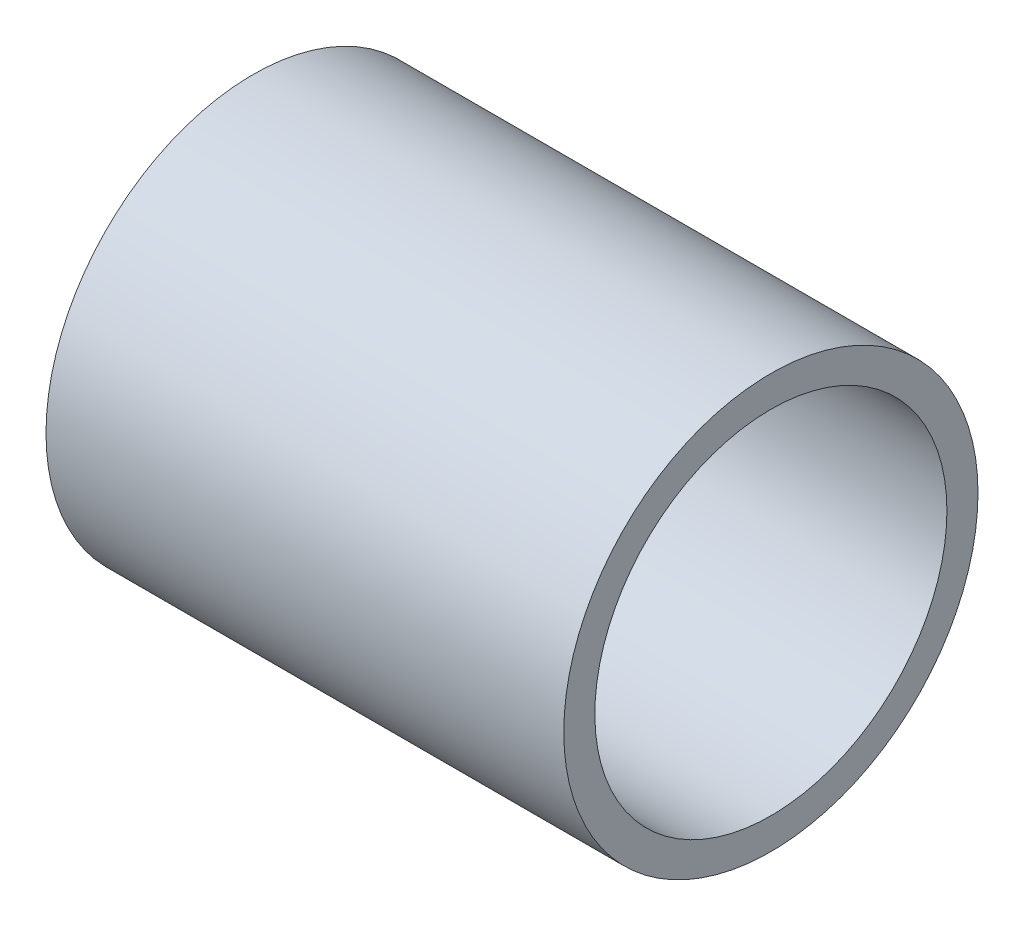
SolidWorks part; units mm, degrees
ref_plane "前基準面" through (0, 0, 0) normal (0, 0, 1) x (1, 0, 0)
ref_plane "上基準面" through (0, 0, 0) normal (0, 1, 0) x (1, 0, 0)
ref_plane "右基準面" through (0, 0, 0) normal (1, 0, 0) x (0, 0, -1)
sketch "草圖1" plane through (0, 0, 0) normal (1, 0, 0) x (0, 0, -1)
  circle A0 centre (0, 0) radius 10
  circle A1 centre (0, 0) radius 8.5
  dimension "D1" = 20
  dimension "D2" = 17
extrude "填料-伸長1" add sketch "草圖1" along normal blind 20
sketch "草圖2" plane through (0, 0, 0) normal (-1, 0, 0) x (0, 0, 1)
  line L5 (0, 0) -> (-3.6, 0)
  line L6 (-3.6, 7.7) -> (-3.6, -7.7)
  circle A0 centre (0, 0) radius 8.5 construction
  arc A1 (-6.26, -5.75) -> (-6.26, 5.75) centre (0, 0) ccw
  circle A2 centre (0, 0) radius 8.5
  dimension "D1" = 3.6
sketch "草圖4" plane through (0, 0, 0) normal (-1, 0, 0) x (0, 0, 1)
  circle A0 centre (0, 0) radius 10
  circle A1 centre (0, 0) radius 8.5
extrude "填料-伸長7" add sketch "草圖2" along normal blind 5 separate body
extrude "填料-伸長8" add sketch "草圖4" along normal blind 5
